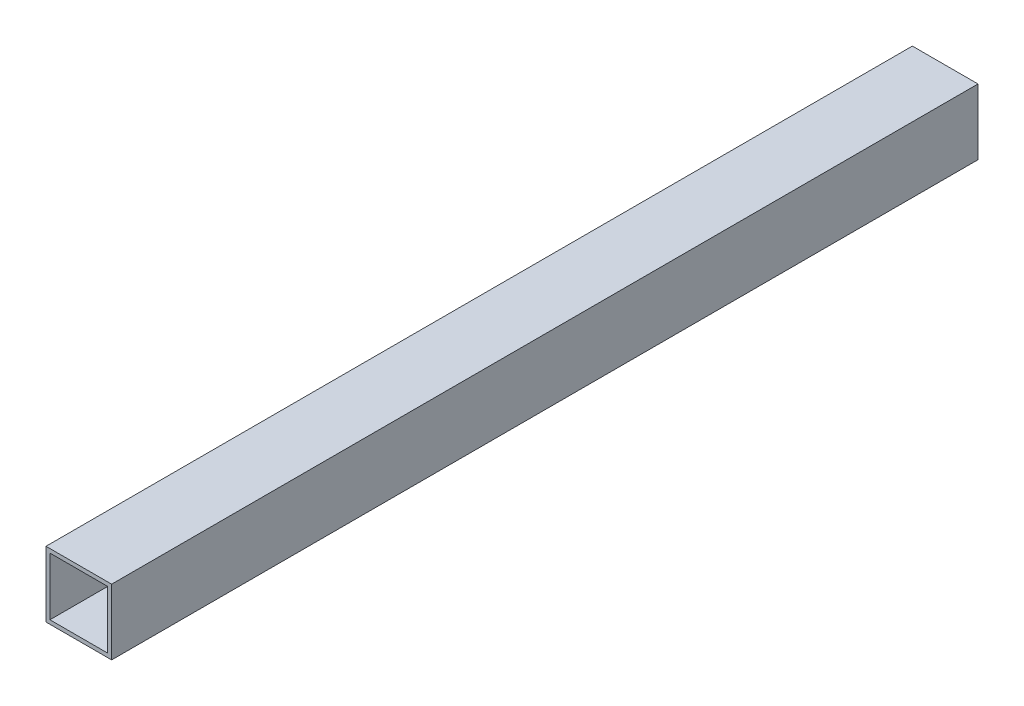
SolidWorks part; units mm, degrees
ref_plane "Front" through (0, 0, 0) normal (0, 0, 1) x (1, 0, 0)
ref_plane "Top" through (0, 0, 0) normal (0, 1, 0) x (1, 0, 0)
ref_plane "Right" through (0, 0, 0) normal (1, 0, 0) x (0, 0, -1)
sketch "Эскиз1" plane through (0, 0, 0) normal (0, 0, 1) x (1, 0, 0)
  line L1 (-12.5, -12.5) -> (12.5, -12.5)
  line L2 (-12.5, -12.5) -> (-12.5, 12.5)
  line L3 (-12.5, 12.5) -> (12.5, 12.5)
  line L4 (12.5, -12.5) -> (12.5, 12.5)
  line L5 (-12.5, -12.5) -> (12.5, 12.5) construction
  line L6 (-12.5, 12.5) -> (12.5, -12.5) construction
  point P0 (0, 0)
  dimension "D1" = 25
  dimension "D2" = 25
extrude "Вытянуть-Тонкостенный1" add sketch "Эскиз1" along normal blind 330 thin thin type one direction reverse wall 1.5
